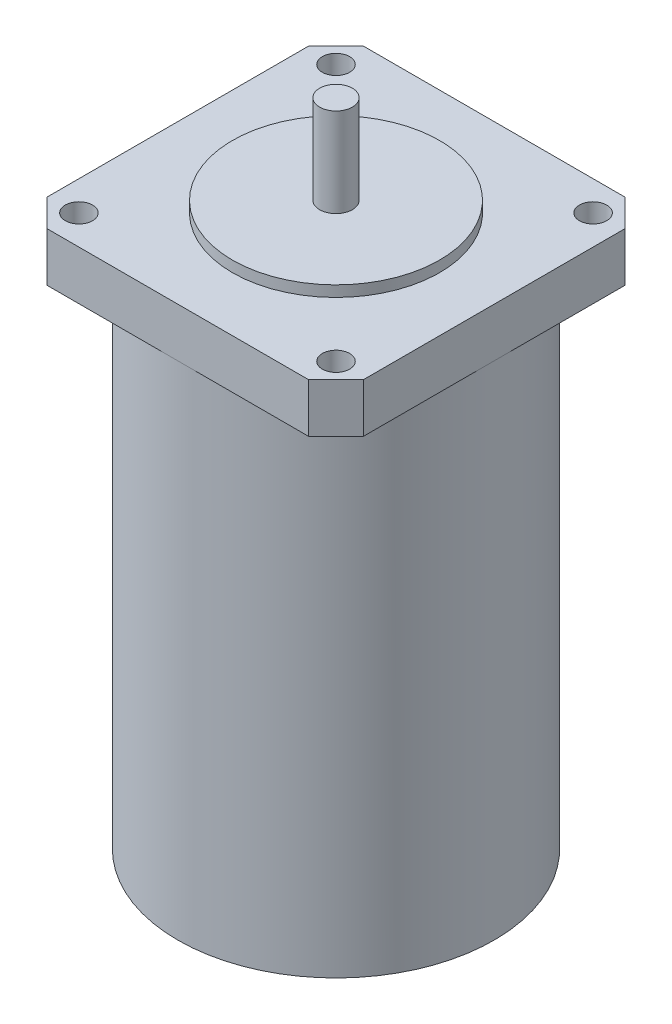
SolidWorks part; units mm, degrees
ref_plane "Front Plane" through (0, 0, 0) normal (0, 0, 1) x (1, 0, 0)
ref_plane "Top Plane" through (0, 0, 0) normal (0, 1, 0) x (1, 0, 0)
ref_plane "Right Plane" through (0, 0, 0) normal (1, 0, 0) x (0, 0, -1)
sketch "Sketch2" plane through (0, 0, 0) normal (0, 1, 0) x (1, 0, 0)
  circle A0 centre (0, 0) radius 29
  dimension "D1" = 58
extrude "Boss-Extrude1" add sketch "Sketch2" along normal blind 101
sketch "Sketch3" plane through (0, 101, 0) normal (0, 1, 0) x (1, 0, 0)
  line L0 (-29, 24) -> (-24, 29)
  line L1 (-24, -29) -> (24, -29)
  line L2 (-29, -24) -> (-29, 24)
  line L3 (-24, 29) -> (24, 29)
  line L4 (29, -24) -> (29, 24)
  line L5 (-29, -29) -> (29, 29) construction
  line L6 (-29, 29) -> (29, -29) construction
  line L7 (-24, -29) -> (-29, -24)
  line L8 (24, -29) -> (29, -24)
  line L9 (24, 29) -> (29, 24)
  circle A0 centre (-23.57, 23.57) radius 2.5
  circle A1 centre (23.57, 23.57) radius 2.5
  circle A2 centre (23.57, -23.57) radius 2.5
  circle A3 centre (-23.57, -23.57) radius 2.5
  point P0 (0, 0)
  point P17 (0, 0)
  dimension "D2" = 4
  dimension "D1" = 58
  dimension "D3" = 47.14
extrude "Boss-Extrude2" add sketch "Sketch3" against normal blind 9
sketch "Sketch4" plane through (0, 101, 0) normal (0, 1, 0) x (1, 0, 0)
  circle A0 centre (0, 0) radius 19
extrude "Boss-Extrude3" add sketch "Sketch4" along normal blind 2
sketch "Sketch5" plane through (0, 103, 0) normal (0, 1, 0) x (1, 0, 0)
  circle A0 centre (0, 0) radius 3
extrude "Boss-Extrude4" add sketch "Sketch5" along normal blind 16.3
